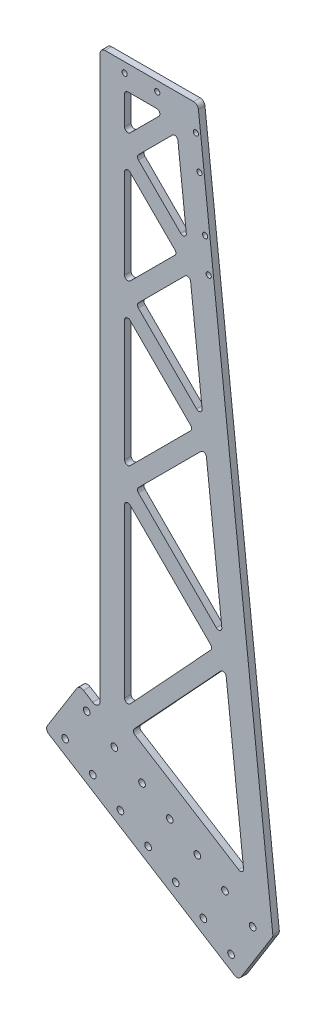
SolidWorks part; units mm, degrees
ref_plane "前视基准面" through (0, 0, 0) normal (0, 0, 1) x (1, 0, 0)
ref_plane "上视基准面" through (0, 0, 0) normal (0, 1, 0) x (1, 0, 0)
ref_plane "右视基准面" through (0, 0, 0) normal (1, 0, 0) x (0, 0, -1)
other "Configuration Table"
sketch "草图1" plane through (0, 0, 0) normal (0, 0, 1) x (1, 0, 0)
  line L0 (0, 0) -> (1032.2158, 0) construction
  line L1 (1032.2158, 0) -> (0, 645) construction
  line L2 (0, 645) -> (0, 0) construction
  line L3 (0, 645) -> (0, 1045)
  line L4 (0, 645) -> (84.8048, 592.0081)
  line L5 (0, 645) -> (21.1968, 678.9219)
  line L6 (84.8048, 592.0081) -> (106.0016, 625.93)
  line L7 (21.1968, 678.9219) -> (106.0016, 625.93)
  line L8 (0, 1045) -> (60, 1045)
  line L9 (21.1968, 678.9219) -> (0, 645)
  line L10 (60, 1045) -> (106.0016, 625.93)
  line L11 (21.1968, 678.9219) -> (-12.7252, 700.1187)
  line L12 (0, 645) -> (-33.9219, 666.1968)
  line L13 (-12.7252, 700.1187) -> (-33.9219, 666.1968)
  point P4 (0, 645)
  point P10 (0, 645)
  point P13 (0, 0)
  point P14 (0, 645)
  point P15 (4.2358, 645)
  point P16 (0, 0)
  dimension "D1" = 32
  dimension "D2" = 645
  dimension "D3" = 40
  dimension "D4" = 100
  dimension "D5" = 400
  dimension "D6" = 60
  dimension "D7" = 40
extrude "凸台-拉伸1" add sketch "草图1" along normal blind 4
sketch "草图2" plane through (0, 0, 4) normal (0, 0, 1) x (1, 0, 0)
  line L0 (-33.9219, 666.1968) -> (84.8048, 592.0081) construction
  line L1 (-33.9219, 666.1968) -> (-12.7252, 700.1187) construction
  line L2 (84.8048, 592.0081) -> (106.0016, 625.93) construction
  line L3 (-12.7252, 700.1187) -> (106.0016, 625.93) construction
  line L4 (0, 692.1671) -> (-12.7252, 700.1187) construction
  line L5 (-23.3235, 683.1577) -> (95.4032, 608.969) construction
  line L6 (-16.6995, 693.7583) -> (102.0272, 619.5696) construction
  line L7 (-29.9475, 672.5571) -> (88.7792, 598.3684) construction
  line L8 (-8.2191, 688.4591) -> (-21.467, 667.2579) construction
  circle A0 centre (-8.2191, 688.4591) radius 2.05
  circle A1 centre (-21.467, 667.2579) radius 2.05
  circle A2 centre (-4.5061, 656.6596) radius 2.05
  circle A3 centre (8.7419, 677.8608) radius 2.05
  circle A4 centre (12.4549, 646.0612) radius 2.05
  circle A5 centre (25.7029, 667.2624) radius 2.05
  circle A6 centre (29.4158, 635.4628) radius 2.05
  circle A7 centre (42.6638, 656.664) radius 2.05
  circle A8 centre (46.3768, 624.8644) radius 2.05
  circle A9 centre (59.6248, 646.0656) radius 2.05
  circle A10 centre (63.3378, 614.266) radius 2.05
  circle A11 centre (76.5857, 635.4672) radius 2.05
  circle A12 centre (80.2987, 603.6676) radius 2.05
  circle A13 centre (93.5467, 624.8688) radius 2.05
  dimension "D3" = 4.1
  dimension "D1" = 12.5
  dimension "D2" = 12.5
  dimension "D4" = 10
  dimension "D5" = 7
extrude "切除-拉伸1" cut sketch "草图2" against normal through all
fillet "圆角2" radius 3 7 edges at (0, 1045, 2) (60, 1045, 2) (106.0016, 625.93, 2) (84.8048, 592.0081, 2) (-33.9219, 666.1968, 2) (-12.7252, 700.1187, 2) (0, 692.1671, 2)
sketch "草图3" plane through (0, 0, 0) normal (0, 0, -1) x (-1, 0, 0)
  line L0 (-15, 1030) -> (-46.5565, 1030)
  line L1 (-46.5565, 1030) -> (-88.4105, 648.7139)
  line L2 (-88.4105, 648.7139) -> (-15, 694.5859)
  line L3 (-15, 694.5859) -> (-15, 1030)
  line L4 (-3, 1045) -> (-57.3113, 1045) construction
  line L5 (-60.2934, 1042.3273) -> (-105.888, 626.9645) construction
  line L6 (0, 697.5793) -> (0, 1042) construction
  line L7 (4.5898, 695.0351) -> (10.181, 698.5289) construction
  line L8 (-46.5565, 1030) -> (-15, 998.4435)
  line L9 (-15, 998.4435) -> (-54.3387, 959.1049)
  line L10 (-54.3387, 959.1049) -> (-15, 919.7662)
  line L11 (-15, 919.7662) -> (-64.04, 870.7262)
  line L12 (-64.04, 870.7262) -> (-15, 821.6861)
  line L13 (-15, 821.6861) -> (-76.1339, 760.5522)
  line L14 (-76.1339, 760.5522) -> (-15, 694.5859)
  line L15 (-50.092, 1026.4645) -> (-22.0711, 998.4435)
  line L16 (-22.0711, 998.4435) -> (-61.4097, 959.1049)
  line L17 (-61.4097, 959.1049) -> (-22.0711, 919.7662)
  line L18 (-22.0711, 919.7662) -> (-71.1111, 870.7262)
  line L19 (-71.1111, 870.7262) -> (-22.0711, 821.6861)
  line L20 (-22.0711, 821.6861) -> (-83.0731, 760.6841)
  line L21 (-83.0731, 760.6841) -> (-18.6673, 691.1872)
  line L22 (-43.0209, 1033.5355) -> (-7.9289, 998.4435)
  line L23 (-7.9289, 998.4435) -> (-47.2676, 959.1049)
  line L24 (-47.2676, 959.1049) -> (-7.9289, 919.7662)
  line L25 (-7.9289, 919.7662) -> (-56.969, 870.7262)
  line L26 (-56.969, 870.7262) -> (-7.9289, 821.6861)
  line L27 (-7.9289, 821.6861) -> (-69.1947, 760.4203)
  line L28 (-69.1947, 760.4203) -> (-11.3327, 697.9845)
  dimension "D1" = 15
  dimension "D2" = 10
  dimension "D3" = 15
  dimension "D4" = 15
  dimension "D5" = 45
  dimension "D6" = 5
  dimension "D7" = 5
extrude "切除-拉伸2" cut sketch "草图3" against normal through all contours L0 L22 L3 | L16 L15 L1 | L23 L24 L3 | L18 L17 L1 | L25 L26 L3 | L20 L19 L1 | L27 L28 L3 | L21 L1 L2
fillet "圆角3" radius 2 24 edges at (76.8559, 753.9754, 2) (88.4105, 648.7139, 2) (19.317, 691.8883, 2) (15, 814.6151, 2) (15, 701.9417, 2) (69.1947, 760.4203, 2) (64.7395, 864.3545, 2) (75.262, 768.4952, 2) (22.0711, 821.6861, 2) (15, 828.7572, 2) (56.969, 870.7262, 2) (15, 912.6952, 2) (22.0711, 919.7662, 2) (55.0381, 952.7332, 2) (63.1681, 878.6691, 2) (15, 926.8373, 2) (15, 991.3725, 2) (47.2676, 959.1049, 2) (53.4668, 967.0479, 2) (22.0711, 998.4435, 2) (47.2559, 1023.6284, 2) (39.4854, 1030, 2) (15, 1030, 2) (15, 1005.5146, 2)
sketch "草图4" plane through (0, 0, 0) normal (0, 0, -1) x (-1, 0, 0)
  circle A0 centre (-35, 1039) radius 1.6
  circle A1 centre (-15, 1039) radius 1.6
extrude "切除-拉伸3" cut sketch "草图4" against normal through all
sketch "草图5" plane through (0, 0, 0) normal (0, 0, -1) x (-1, 0, 0)
  circle A0 centre (-60.9121, 1009.197) radius 1.6
  circle A1 centre (-58.7298, 1029.0776) radius 1.6
  circle A2 centre (-64.4038, 977.3881) radius 1.6
  circle A3 centre (-66.5861, 957.5075) radius 1.6
extrude "切除-拉伸4" cut sketch "草图5" against normal through all
